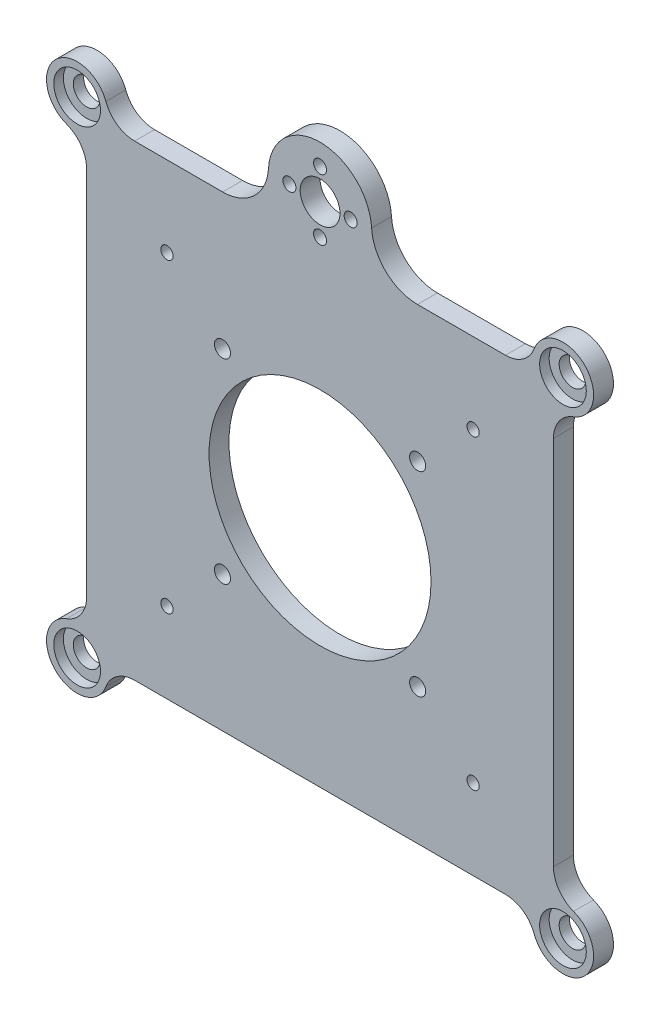
SolidWorks part; units mm, degrees
ref_plane "前视基准面" through (0, 0, 0) normal (0, 0, 1) x (1, 0, 0)
ref_plane "上视基准面" through (0, 0, 0) normal (0, 1, 0) x (1, 0, 0)
ref_plane "右视基准面" through (0, 0, 0) normal (1, 0, 0) x (0, 0, -1)
sketch "草图1" plane through (0, 0, 0) normal (0, 0, 1) x (1, 0, 0)
  line L0 (-48.4591, -61) -> (48.4591, -61)
  line L1 (61, -48.4591) -> (61, 48.4591)
  line L2 (48.4591, 61) -> (25.4558, 61)
  line L3 (-61, 48.4591) -> (-61, -48.4591)
  line L4 (-48.4591, 61) -> (-25.4558, 61)
  arc A0 (-55.967, 66.2374) -> (-66.2374, 55.967) centre (-63.4749, 63.4749) ccw
  arc A1 (-55.967, 66.2374) -> (-48.4591, 61) centre (-48.4591, 69) ccw
  arc A2 (-61, 48.4591) -> (-66.2374, 55.967) centre (-69, 48.4591) ccw
  arc A3 (66.2374, 55.967) -> (55.967, 66.2374) centre (63.4749, 63.4749) ccw
  arc A4 (66.2374, 55.967) -> (61, 48.4591) centre (69, 48.4591) ccw
  arc A5 (48.4591, 61) -> (55.967, 66.2374) centre (48.4591, 69) ccw
  arc A6 (55.967, -66.2374) -> (66.2374, -55.967) centre (63.4749, -63.4749) ccw
  arc A7 (61, -48.4591) -> (66.2374, -55.967) centre (69, -48.4591) ccw
  arc A8 (55.967, -66.2374) -> (48.4591, -61) centre (48.4591, -69) ccw
  arc A9 (-66.2374, -55.967) -> (-55.967, -66.2374) centre (-63.4749, -63.4749) ccw
  arc A10 (-48.4591, -61) -> (-55.967, -66.2374) centre (-48.4591, -69) ccw
  arc A11 (-66.2374, -55.967) -> (-61, -48.4591) centre (-69, -48.4591) ccw
  arc A12 (13.4766, 72.2941) -> (-13.4766, 72.2941) centre (0, 71.5) ccw
  arc A13 (-25.4558, 61) -> (-13.4766, 72.2941) centre (-25.4558, 73) ccw
  arc A14 (13.4766, 72.2941) -> (25.4558, 61) centre (25.4558, 73) ccw
  point P38 (0, 0.001)
  point P39 (0.001, 0.001)
  point P40 (0.001, 0)
extrude "凸台-拉伸1" add sketch "草图1" along normal blind 5.2
sketch "草图2" plane through (0, 0, 5.2) normal (0, 0, 1) x (1, 0, 0)
  circle A0 centre (-63.4749, 63.4749) radius 6.1
  circle A1 centre (63.4749, 63.4749) radius 6.1
  circle A2 centre (63.4749, -63.4749) radius 6.1
  circle A3 centre (-63.4749, -63.4749) radius 6.1
extrude "切除-拉伸1" cut sketch "草图2" against normal blind 2.5
sketch "草图3" plane through (0, 0, 5.2) normal (0, 0, 1) x (1, 0, 0)
  circle A0 centre (0, 71.5) radius 5.2
extrude "切除-拉伸2" cut sketch "草图3" against normal blind 6
sketch "草图4" plane through (0, 0, 5.2) normal (0, 0, 1) x (1, 0, 0)
  circle A0 centre (8, 71.5) radius 1.7
  circle A1 centre (0, 79.5) radius 1.7
  circle A2 centre (-8, 71.5) radius 1.7
  circle A3 centre (0, 63.5) radius 1.7
extrude "切除-拉伸3" cut sketch "草图4" against normal blind 6
sketch "草图5" plane through (0, 0, 5.2) normal (0, 0, 1) x (1, 0, 0)
  circle A0 centre (-40, 40) radius 1.6
  circle A1 centre (40, 40) radius 1.6
  circle A2 centre (40, -40) radius 1.6
  circle A3 centre (-40, -40) radius 1.6
  circle A4 centre (-25.5, 25.5) radius 2.1
  circle A5 centre (25.5, 25.5) radius 2.1
  circle A6 centre (25.5, -25.5) radius 2.1
  circle A7 centre (-25.5, -25.5) radius 2.1
extrude "切除-拉伸4" cut sketch "草图5" against normal blind 6
sketch "草图6" plane through (0, 0, 5.2) normal (0, 0, 1) x (1, 0, 0)
  circle A0 centre (0, 0) radius 29
extrude "切除-拉伸5" cut sketch "草图6" against normal blind 6
sketch "草图7" plane through (0, 0, 2.7) normal (0, 0, 1) x (1, 0, 0)
  circle A0 centre (-63.4749, 63.4749) radius 3.5
  circle A1 centre (63.4749, 63.4749) radius 3.5
  circle A2 centre (-63.4749, -63.4749) radius 3.5
  circle A3 centre (63.4749, -63.4749) radius 3.5
extrude "切除-拉伸6" cut sketch "草图7" against normal blind 10
